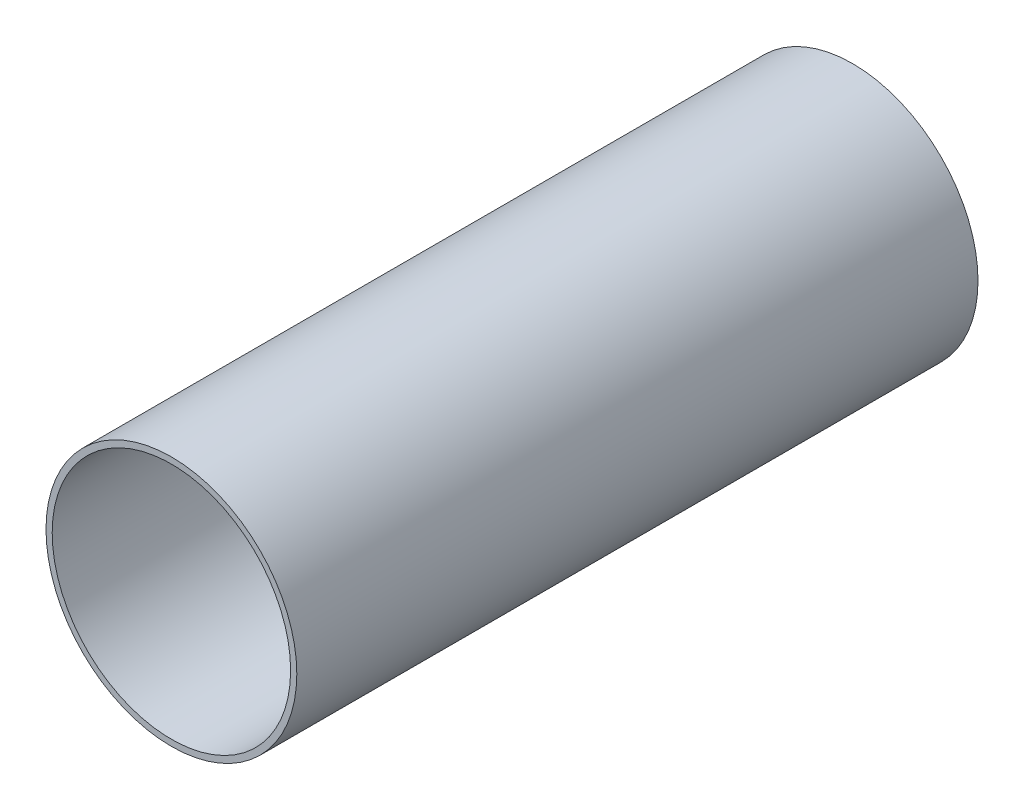
SolidWorks part; units mm, degrees
ref_plane "Front Plane" through (0, 0, 0) normal (0, 0, 1) x (1, 0, 0)
ref_plane "Top Plane" through (0, 0, 0) normal (0, 1, 0) x (1, 0, 0)
ref_plane "Right Plane" through (0, 0, 0) normal (1, 0, 0) x (0, 0, -1)
sketch "Sketch1" plane through (0, 0, 0) normal (0, 0, 1) x (1, 0, 0)
  circle A0 centre (0, 0) radius 20.25
  circle A1 centre (0, 0) radius 19.25
  dimension "D1" = 38.5
  dimension "D2" = 40.5
extrude "Boss-Extrude1" add sketch "Sketch1" along normal blind 110
